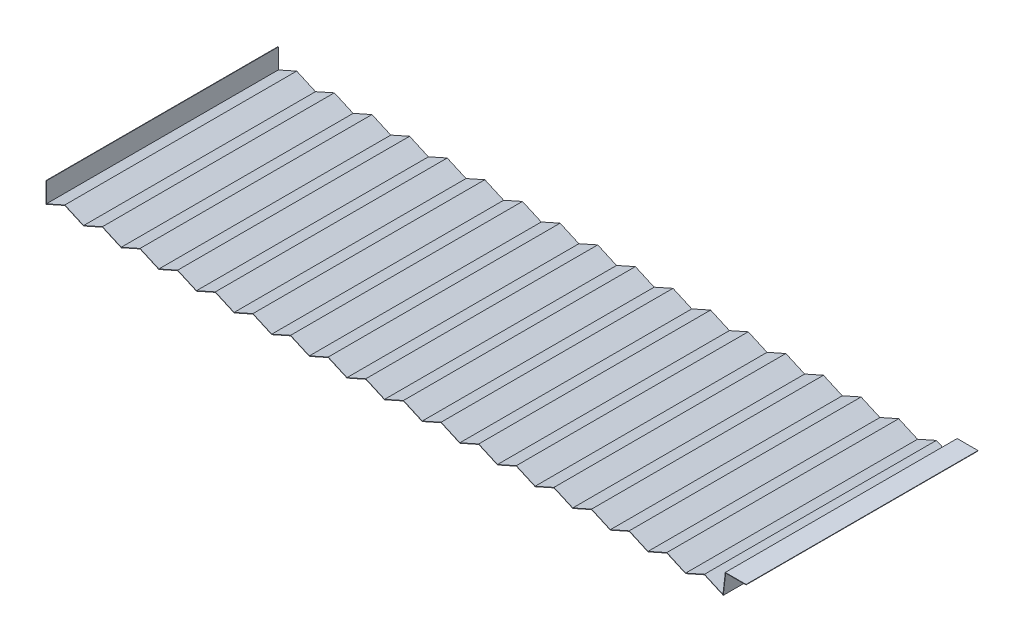
SolidWorks part; units mm, degrees
ref_plane "Front Plane" through (0, 0, 0) normal (0, 0, 1) x (1, 0, 0)
ref_plane "Top Plane" through (0, 0, 0) normal (0, 1, 0) x (1, 0, 0)
ref_plane "Right Plane" through (0, 0, 0) normal (1, 0, 0) x (0, 0, -1)
sketch "Sketch1" plane through (0, 0, 0) normal (0, 0, 1) x (1, 0, 0)
  line L0 (0, 0) -> (13.7921, 6.1472)
  line L1 (13.7921, 6.1472) -> (27.5842, 0)
  line L2 (0, 0) -> (511, 0) construction
  line L3 (27.5842, 0) -> (41.3763, 6.1472)
  line L4 (41.3763, 6.1472) -> (55.1683, 0)
  line L5 (55.1683, 0) -> (68.9604, 6.1472)
  line L6 (68.9604, 6.1472) -> (82.7525, 0)
  line L7 (82.7525, 0) -> (96.5446, 6.1472)
  line L8 (96.5446, 6.1472) -> (110.3367, 0)
  line L9 (110.3367, 0) -> (124.1288, 6.1472)
  line L10 (124.1288, 6.1472) -> (137.9209, 0)
  line L11 (137.9209, 0) -> (151.7129, 6.1472)
  line L12 (151.7129, 6.1472) -> (165.505, 0)
  line L13 (165.505, 0) -> (179.2971, 6.1472)
  line L14 (179.2971, 6.1472) -> (193.0892, 0)
  line L15 (193.0892, 0) -> (206.8813, 6.1472)
  line L16 (206.8813, 6.1472) -> (220.6734, 0)
  line L17 (220.6734, 0) -> (234.4654, 6.1472)
  line L18 (234.4654, 6.1472) -> (248.2575, 0)
  line L19 (0, 0) -> (0, 15.1)
  line L20 (248.2575, 0) -> (262.0496, 6.1472)
  line L21 (262.0496, 6.1472) -> (275.8417, 0)
  line L22 (275.8417, 0) -> (289.6338, 6.1472)
  line L23 (289.6338, 6.1472) -> (303.4259, 0)
  line L24 (303.4259, 0) -> (317.218, 6.1472)
  line L25 (317.218, 6.1472) -> (331.01, 0)
  line L26 (331.01, 0) -> (344.8021, 6.1472)
  line L27 (344.8021, 6.1472) -> (358.5942, 0)
  line L28 (358.5942, 0) -> (372.3863, 6.1472)
  line L29 (372.3863, 6.1472) -> (386.1784, 0)
  line L30 (386.1784, 0) -> (399.9705, 6.1472)
  line L31 (399.9705, 6.1472) -> (413.7626, 0)
  line L32 (413.7626, 0) -> (427.5546, 6.1472)
  line L33 (427.5546, 6.1472) -> (441.3467, 0)
  line L34 (441.3467, 0) -> (455.1388, 6.1472)
  line L35 (455.1388, 6.1472) -> (468.9309, 0)
  line L36 (468.9309, 0) -> (482.723, 6.1472)
  line L37 (482.723, 6.1472) -> (496.5151, 0)
  line L38 (496.5151, 0) -> (498.25, 15)
  line L39 (498.25, 15) -> (513.25, 15)
  line L40 (511.25, -6.7) -> (511.25, 14.3) construction
  dimension "D1" = 511
  dimension "D2" = 15.1
  dimension "D3" = 15
  dimension "D4" = 27.5842
  dimension "D6" = 15
  dimension "D7" = 2
  dimension "D5" = 18
extrude "Extrude-Thin1" add sketch "Sketch1" along normal mid plane 170 thin thin type one direction reverse wall 0.3
